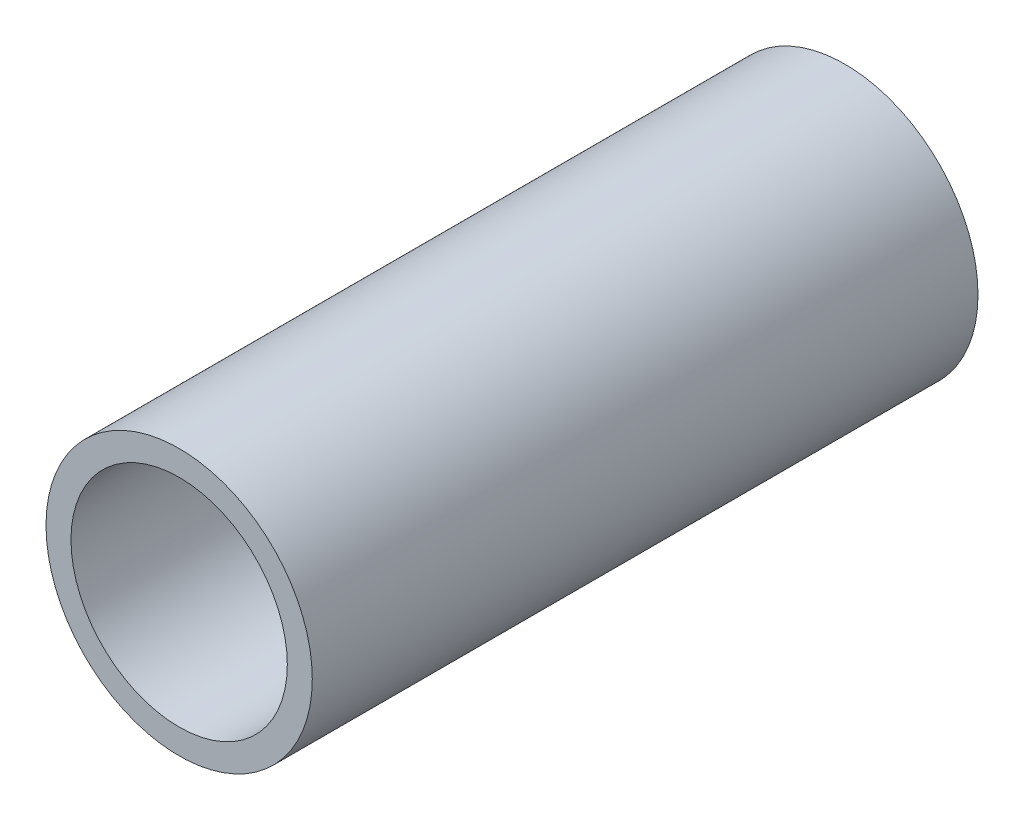
SolidWorks part; units mm, degrees
ref_plane "Plan de face" through (0, 0, 0) normal (0, 0, 1) x (1, 0, 0)
ref_plane "Plan de dessus" through (0, 0, 0) normal (0, 1, 0) x (1, 0, 0)
ref_plane "Plan de droite" through (0, 0, 0) normal (1, 0, 0) x (0, 0, -1)
sketch "Esquisse1" plane through (0, 0, 0) normal (0, 0, 1) x (1, 0, 0)
  circle A0 centre (0, 0) radius 6.5
  circle A1 centre (0, 0) radius 8
  dimension "D1" = 13
  dimension "D2" = 16
extrude "Boss.-Extru.1" add sketch "Esquisse1" along normal blind 40
